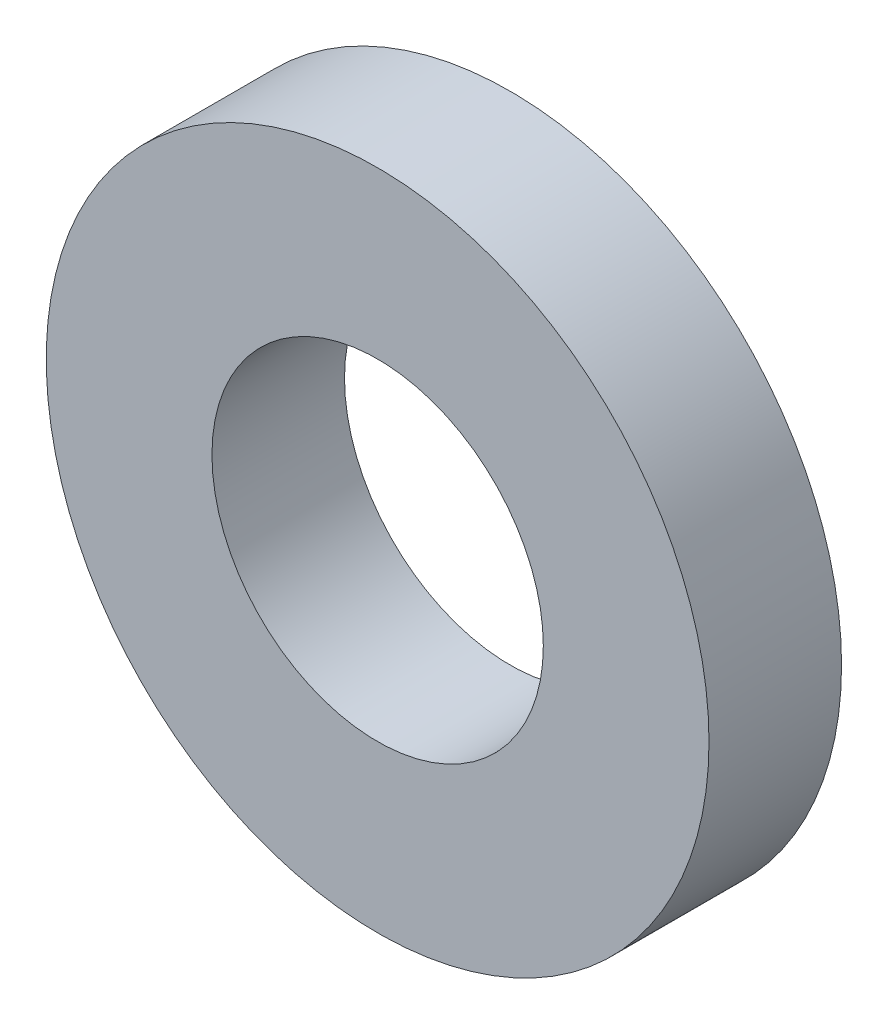
SolidWorks part; units mm, degrees
ref_plane "Front Plane" through (0, 0, 0) normal (0, 0, 1) x (1, 0, 0)
ref_plane "Top Plane" through (0, 0, 0) normal (0, 1, 0) x (1, 0, 0)
ref_plane "Right Plane" through (0, 0, 0) normal (1, 0, 0) x (0, 0, -1)
sketch "Sketch1" plane through (0, 0, 0) normal (0, 0, 1) x (1, 0, 0)
  circle A0 centre (0, 0) radius 5
  dimension "D1" = 10
extrude "Boss-Extrude1" add sketch "Sketch1" along normal blind 2
sketch "Sketch2" plane through (0, 0, 2) normal (0, 0, 1) x (1, 0, 0)
  circle A0 centre (0, 0) radius 2.5
  dimension "D1" = 5
extrude "Cut-Extrude1" cut sketch "Sketch2" against normal through all
